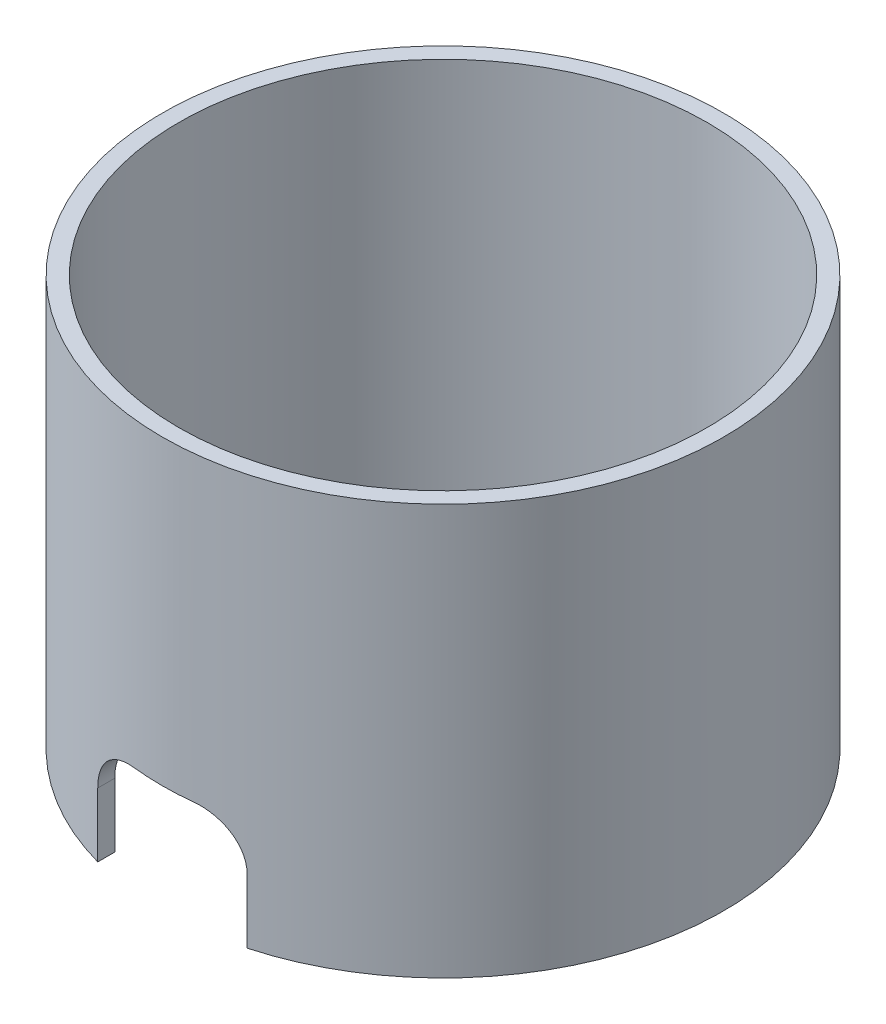
SolidWorks part; units mm, degrees
material "E-Glass Fiber"
ref_plane "Front Plane" through (0, 0, 0) normal (0, 0, 1) x (1, 0, 0)
ref_plane "Top Plane" through (0, 0, 0) normal (0, 1, 0) x (1, 0, 0)
ref_plane "Right Plane" through (0, 0, 0) normal (1, 0, 0) x (0, 0, -1)
sketch "Sketch1" plane through (0, 0, 0) normal (0, 1, 0) x (1, 0, 0)
  circle A0 centre (0, 0) radius 805
  circle A1 centre (0, 0) radius 855
  dimension "D1" = 1610
  dimension "D2" = 50
extrude "Boss-Extrude1" add sketch "Sketch1" along normal blind 1300
sketch "Sketch2" plane through (0, 0, 0) normal (0, 0, 1) x (1, 0, 0)
  line L0 (0, 280) -> (0, 1300) construction
  line L1 (92.5614, 280) -> (-92.5614, 280) construction
  line L2 (-177.5614, 195) -> (-177.5614, -45) construction
  line L3 (-92.5614, -130) -> (92.5614, -130) construction
  line L4 (177.5614, -45) -> (177.5614, 195) construction
  line L5 (92.5614, 330) -> (-92.5614, 330)
  line L6 (-227.5614, 195) -> (-227.5614, -45)
  line L7 (-92.5614, -180) -> (92.5614, -180)
  line L8 (227.5614, -45) -> (227.5614, 195)
  arc A0 (177.5614, 195) -> (92.5614, 280) centre (92.5614, 195) ccw construction
  arc A1 (-92.5614, 280) -> (-177.5614, 195) centre (-92.5614, 195) ccw construction
  arc A2 (-177.5614, -45) -> (-92.5614, -130) centre (-92.5614, -45) ccw construction
  arc A3 (92.5614, -130) -> (177.5614, -45) centre (92.5614, -45) ccw construction
  arc A4 (-92.5614, 330) -> (-227.5614, 195) centre (-92.5614, 195) ccw
  arc A5 (-227.5614, -45) -> (-92.5614, -180) centre (-92.5614, -45) ccw
  arc A6 (92.5614, -180) -> (227.5614, -45) centre (92.5614, -45) ccw
  arc A7 (227.5614, 195) -> (92.5614, 330) centre (92.5614, 195) ccw
  dimension "D3" = 85
  dimension "D1" = 355.1228
  dimension "D2" = 410
  dimension "D4" = 1020
  dimension "D5" = 50
extrude "Cut-Extrude1" cut sketch "Sketch2" along normal blind 2646
sketch "Sketch3" plane through (0, 1300, 0) normal (0, 1, 0) x (1, 0, 0)
  circle A1 centre (0, 0) radius 855
  circle A2 centre (0, 0) radius 855
  dimension "D1" = 0
extrude "Cut-Extrude2" cut sketch "Sketch3" against normal blind 50
shell "Shell1" thickness 3
